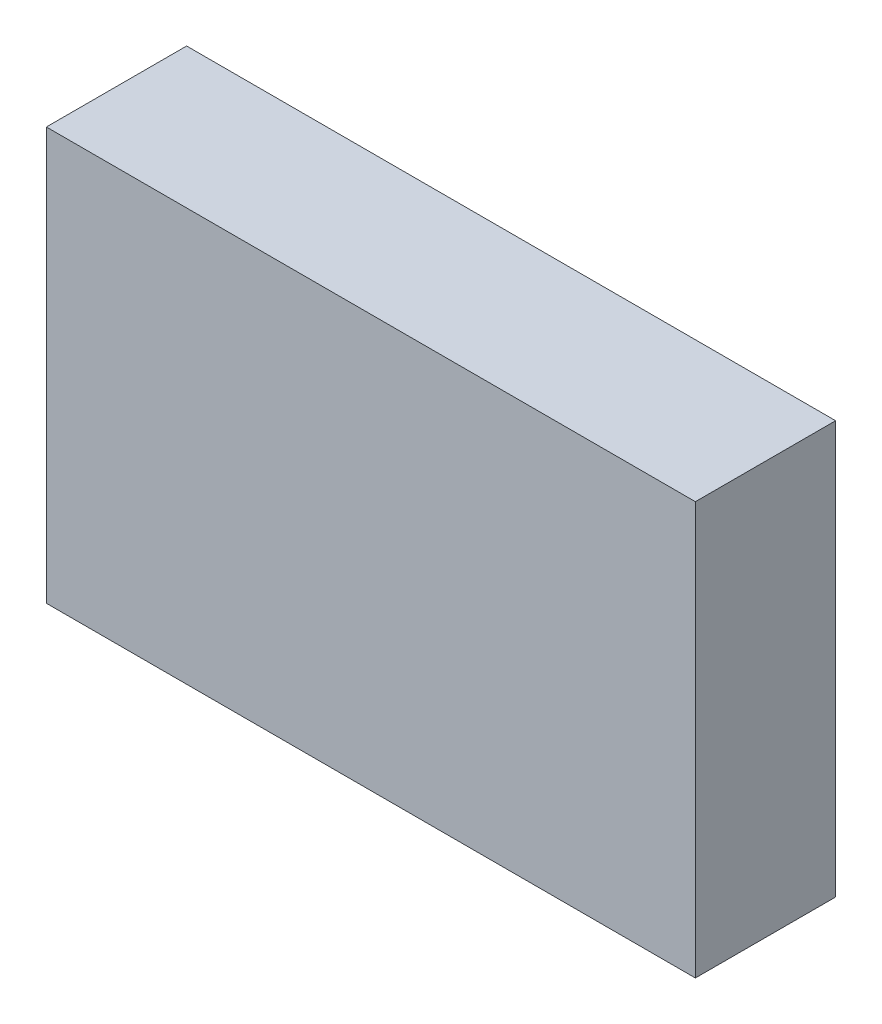
SolidWorks part; units mm, degrees
ref_plane "Front Plane" through (0, 0, 0) normal (0, 0, 1) x (1, 0, 0)
ref_plane "Top Plane" through (0, 0, 0) normal (0, 1, 0) x (1, 0, 0)
ref_plane "Right Plane" through (0, 0, 0) normal (1, 0, 0) x (0, 0, -1)
sketch "Sketch1" plane through (0, 0, 0) normal (0, 0, 1) x (1, 0, 0)
  line L1 (-53.3864, -33.6427) -> (64.6136, -33.6427)
  line L2 (-53.3864, -33.6427) -> (-53.3864, 41.3573)
  line L3 (-53.3864, 41.3573) -> (64.6136, 41.3573)
  line L4 (64.6136, -33.6427) -> (64.6136, 41.3573)
  dimension "D1" = 118
  dimension "D2" = 75
extrude "Boss-Extrude1" add sketch "Sketch1" along normal blind 25.5
